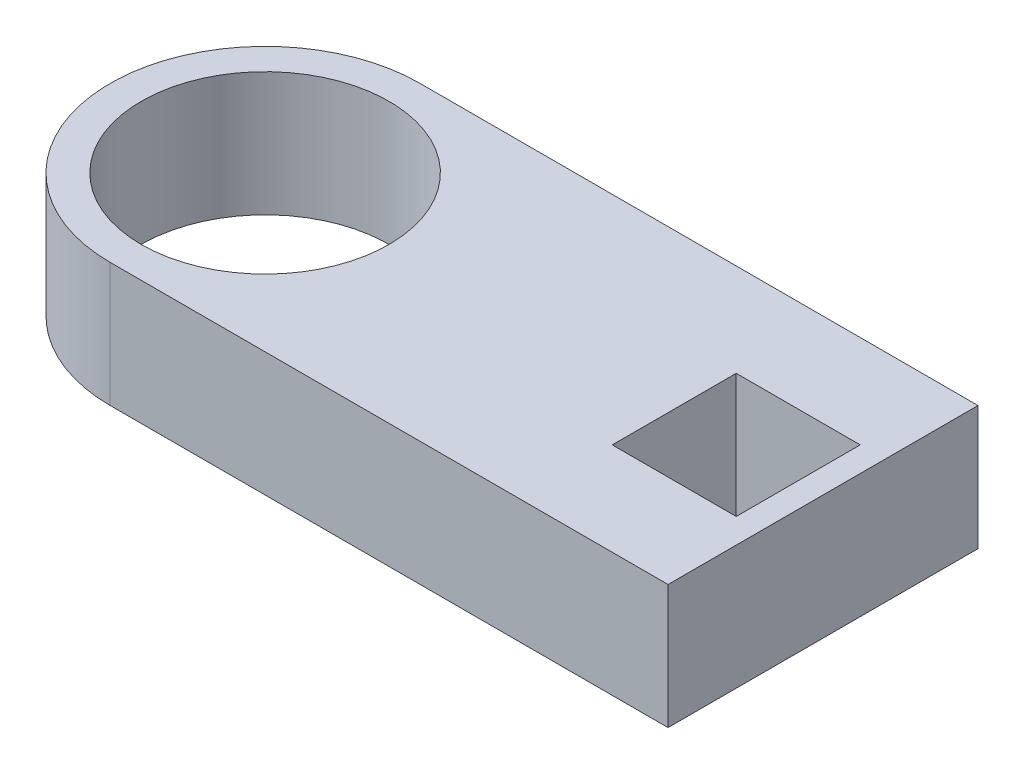
SolidWorks part; units mm, degrees
ref_plane "Front Plane" through (0, 0, 0) normal (0, 0, 1) x (1, 0, 0)
ref_plane "Top Plane" through (0, 0, 0) normal (0, 1, 0) x (1, 0, 0)
ref_plane "Right Plane" through (0, 0, 0) normal (1, 0, 0) x (0, 0, -1)
sketch "Sketch1" plane through (0, 0, 0) normal (0, 1, 0) x (1, 0, 0)
  line L1 (0, 0) -> (45, 0)
  line L3 (0, 25) -> (45, 25)
  line L4 (45, 0) -> (45, 25)
  line L5 (43, 17.5) -> (33, 17.5)
  line L6 (43, 17.5) -> (43, 7.5)
  line L7 (43, 7.5) -> (33, 7.5)
  line L8 (33, 17.5) -> (33, 7.5)
  arc A0 (0, 25) -> (0, 0) centre (0, 12.5) ccw
  circle A1 centre (0, 12.5) radius 10
  dimension "D3" = 20
  dimension "D1" = 45
  dimension "D2" = 25
  dimension "D4" = 10
  dimension "D5" = 7.5
  dimension "D6" = 2
extrude "Boss-Extrude1" add sketch "Sketch1" along normal blind 10
